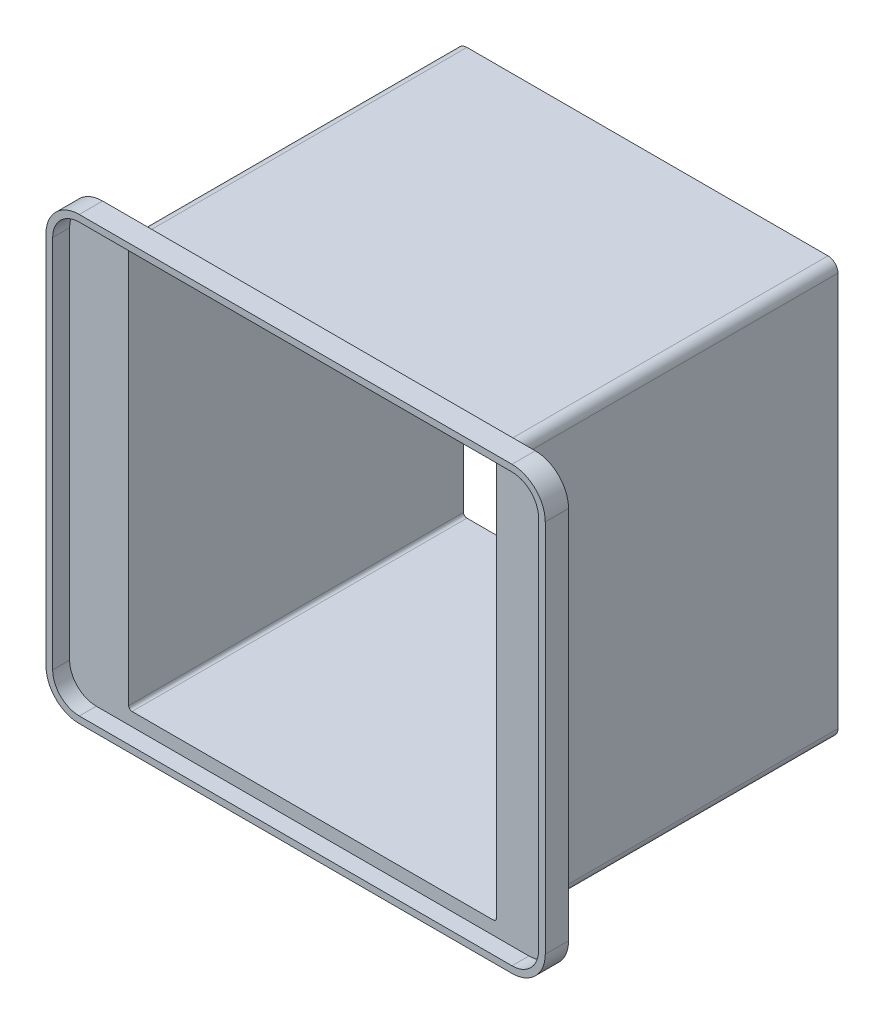
SolidWorks part; units mm, degrees
ref_plane "Front Plane" through (0, 0, 0) normal (0, 0, 1) x (1, 0, 0)
ref_plane "Top Plane" through (0, 0, 0) normal (0, 1, 0) x (1, 0, 0)
ref_plane "Right Plane" through (0, 0, 0) normal (1, 0, 0) x (0, 0, -1)
sketch "Sketch1" plane through (0, 0, 0) normal (0, 0, 1) x (1, 0, 0)
  line L0 (-55.25, 59.25) -> (-55.25, -59.25)
  line L1 (-54.25, 62.25) -> (54.25, 62.25)
  line L2 (-57.25, 59.25) -> (-57.25, -59.25)
  line L3 (-54.25, -62.25) -> (54.25, -62.25)
  line L4 (57.25, 59.25) -> (57.25, -59.25)
  line L5 (-57.25, 62.25) -> (57.25, -62.25) construction
  line L6 (-57.25, -62.25) -> (57.25, 62.25) construction
  line L7 (-54.25, -60.25) -> (54.25, -60.25)
  line L8 (55.25, 59.25) -> (55.25, -59.25)
  line L9 (-54.25, 60.25) -> (54.25, 60.25)
  arc A0 (54.25, 62.25) -> (57.25, 59.25) centre (54.25, 59.25) cw
  arc A1 (-57.25, -59.25) -> (-54.25, -62.25) centre (-54.25, -59.25) ccw
  arc A2 (-54.25, 62.25) -> (-57.25, 59.25) centre (-54.25, 59.25) ccw
  arc A3 (54.25, -62.25) -> (57.25, -59.25) centre (54.25, -59.25) ccw
  arc A4 (-55.25, -59.25) -> (-54.25, -60.25) centre (-54.25, -59.25) ccw
  arc A5 (54.25, -60.25) -> (55.25, -59.25) centre (54.25, -59.25) ccw
  arc A6 (54.25, 60.25) -> (55.25, 59.25) centre (54.25, 59.25) cw
  arc A7 (-54.25, 60.25) -> (-55.25, 59.25) centre (-54.25, 59.25) ccw
  point P0 (0, 0)
  dimension "D3" = 3
  dimension "D1" = 124.5
  dimension "D2" = 114.5
  dimension "D4" = 2
extrude "Boss-Extrude1" add sketch "Sketch1" against normal blind 98.705
sketch "Sketch5" plane through (0, 0, 0) normal (0, 0, 1) x (1, 0, 0)
  line L1 (75, 66.25) -> (-75, 66.25)
  line L2 (75, 66.25) -> (75, -66.25)
  line L3 (75, -66.25) -> (-75, -66.25)
  line L4 (-75, 66.25) -> (-75, -66.25)
  line L5 (75, 66.25) -> (-75, -66.25) construction
  line L6 (75, -66.25) -> (-75, 66.25) construction
  line L14 (-54.25, -60.25) -> (54.25, -60.25) construction
  line L15 (55.25, -59.25) -> (55.25, 59.25) construction
  line L16 (54.25, 60.25) -> (-54.25, 60.25) construction
  line L17 (-55.25, 59.25) -> (-55.25, -59.25) construction
  line L18 (-54.25, -60.25) -> (54.25, -60.25)
  line L19 (55.25, -59.25) -> (55.25, 59.25)
  line L20 (54.25, 60.25) -> (-54.25, 60.25)
  line L21 (-55.25, 59.25) -> (-55.25, -59.25)
  arc A8 (-55.25, -59.25) -> (-54.25, -60.25) centre (-54.25, -59.25) ccw construction
  arc A9 (54.25, -60.25) -> (55.25, -59.25) centre (54.25, -59.25) ccw construction
  arc A10 (55.25, 59.25) -> (54.25, 60.25) centre (54.25, 59.25) ccw construction
  arc A11 (-54.25, 60.25) -> (-55.25, 59.25) centre (-54.25, 59.25) ccw construction
  arc A12 (-55.25, -59.25) -> (-54.25, -60.25) centre (-54.25, -59.25) ccw
  arc A13 (54.25, -60.25) -> (55.25, -59.25) centre (54.25, -59.25) ccw
  arc A14 (55.25, 59.25) -> (54.25, 60.25) centre (54.25, 59.25) ccw
  arc A15 (-54.25, 60.25) -> (-55.25, 59.25) centre (-54.25, 59.25) ccw
  point P0 (0, 0)
  dimension "D1" = 150
  dimension "D2" = 132.5
extrude "Boss-Extrude2" add sketch "Sketch5" along normal blind 7
fillet "Fillet1" radius 10 4 edges at (75, 66.25, 3.5) (75, -66.25, 3.5) (-75, -66.25, 3.5) (-75, 66.25, 3.5)
sketch "Sketch6" plane through (0, 0, 7) normal (0, 0, 1) x (1, 0, 0)
  line L8 (73, -56.25) -> (73, 56.25)
  line L9 (65, 64.25) -> (-65, 64.25)
  line L10 (-73, 56.25) -> (-73, -56.25)
  line L11 (-65, -64.25) -> (65, -64.25)
  line L12 (73, -56.25) -> (73, 56.25)
  line L13 (65, 64.25) -> (-65, 64.25)
  line L14 (-73, 56.25) -> (-73, -56.25)
  line L15 (-65, -64.25) -> (65, -64.25)
  arc A8 (73, 56.25) -> (65, 64.25) centre (65, 56.25) ccw
  arc A9 (-65, 64.25) -> (-73, 56.25) centre (-65, 56.25) ccw
  arc A10 (-73, -56.25) -> (-65, -64.25) centre (-65, -56.25) ccw
  arc A11 (65, -64.25) -> (73, -56.25) centre (65, -56.25) ccw
  arc A12 (73, 56.25) -> (65, 64.25) centre (65, 56.25) ccw
  arc A13 (-65, 64.25) -> (-73, 56.25) centre (-65, 56.25) ccw
  arc A14 (-73, -56.25) -> (-65, -64.25) centre (-65, -56.25) ccw
  arc A15 (65, -64.25) -> (73, -56.25) centre (65, -56.25) ccw
  dimension "D1" = 2
extrude "Cut-Extrude1" cut sketch "Sketch6" against normal blind 5.099
